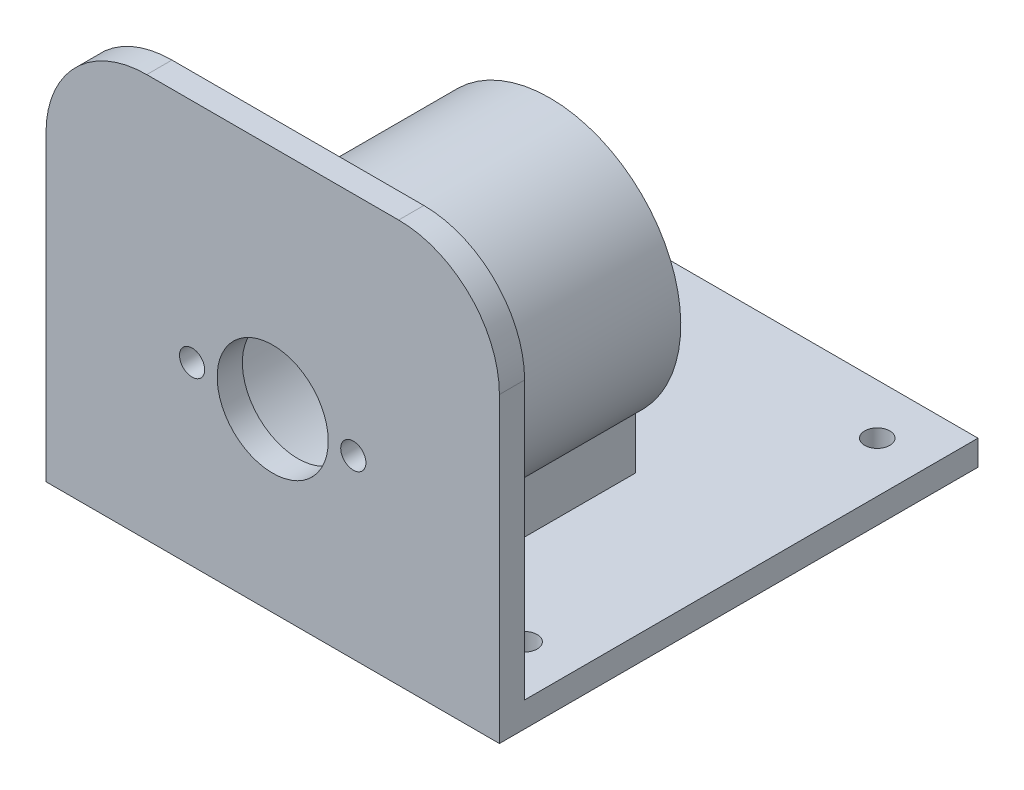
SolidWorks part; units mm, degrees
ref_plane "Alzado" through (0, 0, 0) normal (0, 0, 1) x (1, 0, 0)
ref_plane "Planta" through (0, 0, 0) normal (0, 1, 0) x (1, 0, 0)
ref_plane "Vista lateral" through (0, 0, 0) normal (1, 0, 0) x (0, 0, -1)
sketch "Croquis1" plane through (0, 0, 0) normal (0, 0, 1) x (1, 0, 0)
  line L0 (45, -2.3053) -> (45, -35)
  line L5 (45, -35) -> (-45, -35)
  line L6 (-45, -35) -> (-45, 25)
  line L7 (-25, 45) -> (25, 45)
  line L8 (45, 25) -> (45, -2.3053)
  circle A3 centre (0, 0) radius 11.025
  arc A4 (45, 25) -> (25, 45) centre (25, 25) ccw
  arc A5 (-25, 45) -> (-45, 25) centre (-25, 25) ccw
  point P13 (-45, 45)
  dimension "D2" = 35
  dimension "D3" = 80
  dimension "D4" = 90
  dimension "D1" = 22.05
  dimension "D6" = 20
  dimension "D5" = 45
extrude "Saliente-Extruir1" add sketch "Croquis1" against normal blind 5
sketch "Croquis2" plane through (0, 0, -5) normal (0, 0, -1) x (-1, 0, 0)
  line L0 (45, 25) -> (45, -35) construction
  line L1 (-45, -35) -> (45, -35)
  line L2 (-45, -35) -> (-45, -30)
  line L3 (-45, -30) -> (45, -30)
  line L4 (45, -35) -> (45, -30)
  dimension "D1" = 5
extrude "Saliente-Extruir2" add sketch "Croquis2" along normal blind 90
sketch "Croquis3" plane through (0, 0, -5) normal (0, 0, -1) x (-1, 0, 0)
  line L0 (17, -30) -> (17, -19.6723)
  line L1 (45, -30) -> (-45, -30) construction
  line L2 (45, -30) -> (-45, -30) construction
  line L3 (-17, -30) -> (-17, -19.6723)
  line L4 (-17, -30) -> (17, -30)
  circle A0 centre (0, 0) radius 21.5
  arc A1 (17, -19.6723) -> (-17, -19.6723) centre (0, 0) ccw
  point P9 (0, -30)
  dimension "D1" = 43
  dimension "D4" = 52
  dimension "D2" = 17
  dimension "D3" = 17
extrude "Saliente-Extruir3" add sketch "Croquis3" along normal blind 50
sketch "Croquis4" plane through (0, 0, 0) normal (0, 0, 1) x (1, 0, 0)
  line L0 (0, 0) -> (0, 35.9594) construction
  circle A1 centre (-16, 0) radius 2.5
  circle A2 centre (16, 0) radius 2.5
  dimension "D1" = 16
  dimension "D2" = 5
extrude "Cortar-Extruir1" cut sketch "Croquis4" against normal blind 70
sketch "Croquis5" plane through (0, -30, 0) normal (0, 1, 0) x (1, 0, 0)
  line L0 (45, 50) -> (68.0898, 50) construction
  line L1 (45, 95) -> (45, 5) construction
  line L2 (0, 95) -> (0, 78.3448) construction
  line L3 (-45, 95) -> (45, 95) construction
  line L4 (-45, 95) -> (-45, 5) construction
  circle A0 centre (-35, 85) radius 2.5
  circle A1 centre (35, 85) radius 2.5
  circle A2 centre (35, 15) radius 2.5
  circle A3 centre (-35, 15) radius 2.5
  dimension "D1" = 5
  dimension "D2" = 10
  dimension "D3" = 10
extrude "Cortar-Extruir2" cut sketch "Croquis5" against normal through all
